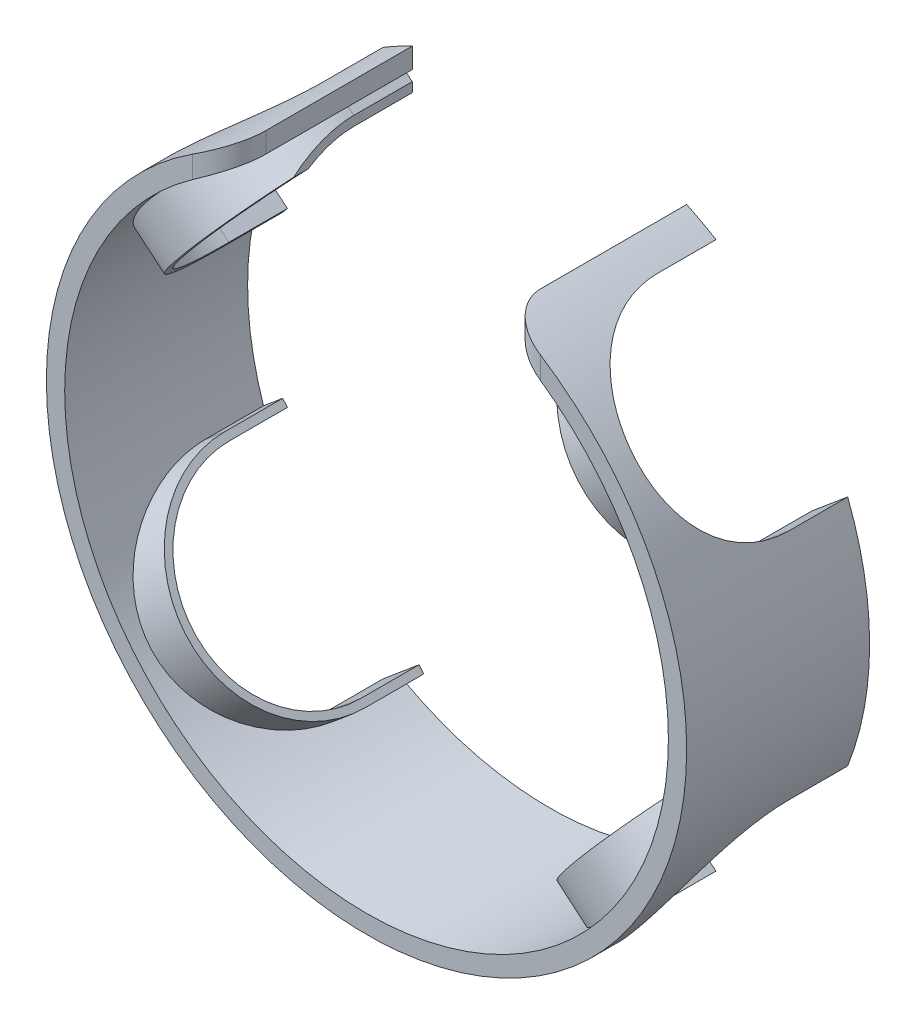
SolidWorks part; units mm, degrees
ref_plane "Front Plane" through (0, 0, 0) normal (0, 0, 1) x (1, 0, 0)
ref_plane "Top Plane" through (0, 0, 0) normal (0, 1, 0) x (1, 0, 0)
ref_plane "Right Plane" through (0, 0, 0) normal (1, 0, 0) x (0, 0, -1)
sketch "Sketch1" plane through (0, 0, 0) normal (0, 0, 1) x (1, 0, 0)
  circle A0 centre (0, 0) radius 87.5
  circle A1 centre (0, 0) radius 82.5
  dimension "D1" = 175
  dimension "D2" = 5
extrude "Boss-Extrude1" add sketch "Sketch1" along normal blind 50
sketch "Sketch2" plane through (0, 0, 0) normal (0, 1, 0) x (1, 0, 0)
  line L0 (0, 0) -> (0, -50)
  line L1 (-87.5, -50) -> (87.5, -50) construction
ref_plane "Plane1" through (0, 0, 0) normal (-0.766, 0.6428, 0) x (0, 0, 1)
sketch "Sketch3" plane through (0, 0, 0) normal (-0.766, 0.6428, 0) x (0, 0, 1)
  line L0 (0, 87.5) -> (0, -87.5) construction
  line L1 (16, 0) -> (0, 0) construction
  line L2 (16, 28) -> (-21.3159, 28)
  line L3 (-21.3159, 28) -> (-21.3159, -28)
  line L4 (-21.3159, -28) -> (16, -28)
  arc A0 (16, -28) -> (16, 28) centre (16, 0) ccw
  dimension "D2" = 56
  dimension "D1" = 16
extrude "Cut-Extrude1" cut sketch "Sketch3" along normal through all
ref_plane "Plane2" through (-53.6231, 44.9951, 0) normal (-0.766, 0.6428, 0) x (0, 0, 1)
sketch "Sketch5" plane through (-53.6231, 44.9951, 0) normal (-0.766, 0.6428, 0) x (0, 0, 1)
  line L0 (0, -28) -> (16, -28) construction
  line L1 (16, 28) -> (0, 28) construction
  line L2 (0, -28) -> (16, -28)
  line L3 (16, 28) -> (0, 28)
  line L4 (0, -30) -> (16, -30)
  line L5 (16, 30) -> (0, 30)
  line L6 (0, 28) -> (0, 30)
  line L7 (0, -28) -> (0, -30)
  arc A0 (16, -28) -> (16, 28) centre (16, 0) ccw construction
  arc A1 (16, -28) -> (16, 28) centre (16, 0) ccw
  arc A2 (16, -30) -> (16, 30) centre (16, 0) ccw
  dimension "D1" = 2
extrude "Boss-Extrude2" add sketch "Sketch5" along normal up to next
mirror "Mirror1" about plane through (0, 0, 0) normal (1, 0, 0) of "Boss-Extrude2", "Cut-Extrude1" second plane through (0, 0, 0) second plane normal (0, 1, 0)
sketch "Sketch4" plane through (0, 0, 50) normal (0, 0, 1) x (1, 0, 0)
  line L1 (-37.5, 150.5063) -> (37.5, 150.5063)
  line L2 (-37.5, 150.5063) -> (-37.5, 0)
  line L3 (-37.5, 0) -> (37.5, 0)
  line L4 (37.5, 150.5063) -> (37.5, 0)
  line L5 (-37.5, 150.5063) -> (37.5, 0) construction
  line L6 (-37.5, 0) -> (37.5, 150.5063) construction
  point P0 (0, 75.2531)
  dimension "D1" = 75
extrude "Cut-Extrude2" cut sketch "Sketch4" against normal through all
fillet "Fillet1" radius 10 2 edges at (-37.5, 76.2708, 50) (37.5, 76.2708, 50)
